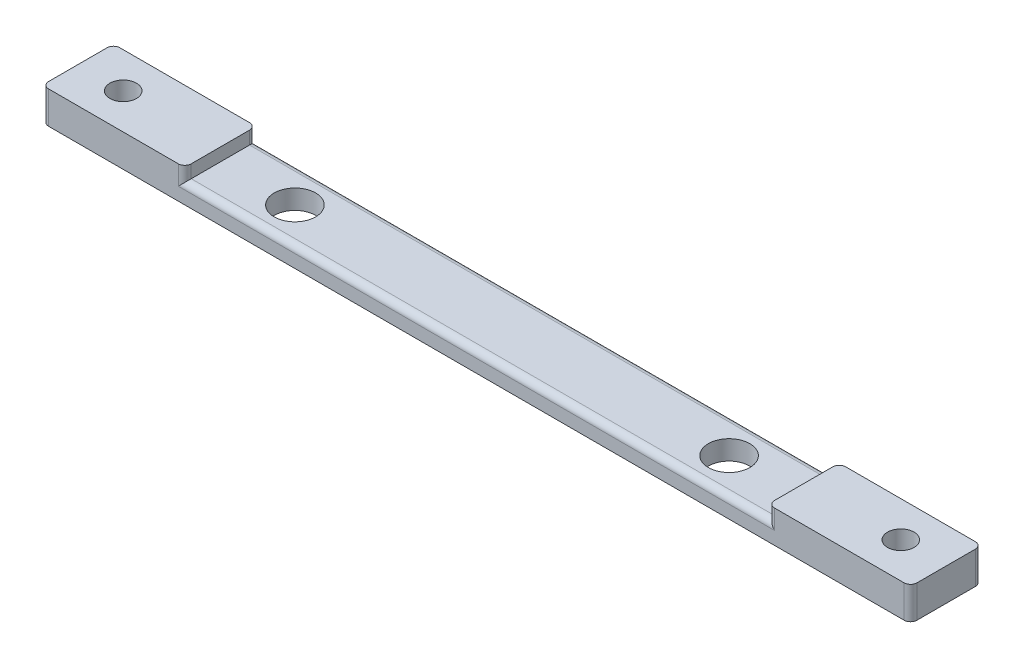
SolidWorks part; units mm, degrees
ref_plane "Plan de face" through (0, 0, 0) normal (0, 0, 1) x (1, 0, 0)
ref_plane "Plan de dessus" through (0, 0, 0) normal (0, 1, 0) x (1, 0, 0)
ref_plane "Plan de droite" through (0, 0, 0) normal (1, 0, 0) x (0, 0, -1)
sketch "Esquisse1" plane through (0, 0, 0) normal (0, 1, 0) x (1, 0, 0)
  line L0 (0, 20.6802) -> (0, -42.2025) construction
  line L1 (0, 0) -> (100.6872, 0) construction
  line L2 (-66, 0) -> (66, 0)
  line L3 (67, 1) -> (67, 10)
  line L4 (66, 11) -> (-66, 11)
  line L5 (24.5168, 5.5) -> (0.5615, 5.5) construction
  line L6 (-67, 1) -> (-67, 10)
  circle A0 centre (60, 5.5) radius 2.05
  circle A1 centre (33.5, 5.5) radius 3.2
  arc A2 (66, 0) -> (67, 1) centre (66, 1) ccw
  arc A3 (67, 10) -> (66, 11) centre (66, 10) ccw
  arc A4 (-67, 10) -> (-66, 11) centre (-66, 10) cw
  arc A5 (-66, 0) -> (-67, 1) centre (-66, 1) cw
  circle A6 centre (-33.5, 5.5) radius 3.2
  circle A7 centre (-60, 5.5) radius 2.05
  point P1 (-67, 11)
  point P9 (0, 0)
  point P17 (67, 0)
  point P20 (67, 11)
  point P31 (0, 11)
  point P32 (-67, 0)
  dimension "D1" = 67
  dimension "D5" = 1
  dimension "D6" = 6.4
  dimension "D7" = 4.1
  dimension "D2" = 33.5
  dimension "D3" = 60
  dimension "D4" = 11
extrude "Boss.-Extru.1" add sketch "Esquisse1" along normal blind 5
sketch "Esquisse2" plane through (0, 0, 0) normal (0, 0, 1) x (1, 0, 0)
  line L0 (0, 18.1819) -> (0, -11.7321) construction
  line L1 (-16.5133, 3) -> (14.2481, 3) construction
  line L2 (-45, 5) -> (-45, 3)
  line L3 (45, 5) -> (45, 3)
  line L4 (-66, 0) -> (66, 0)
  line L5 (66, 0) -> (66, 5)
  line L6 (66, 5) -> (-66, 5)
  line L7 (-66, 5) -> (-66, 0)
  line L8 (-66, 0) -> (66, 0)
  line L9 (66, 0) -> (66, 5)
  line L10 (66, 5) -> (-66, 5)
  line L11 (-66, 5) -> (-66, 0)
  line L12 (-45, 3) -> (45, 3)
  point P13 (0, 3)
  line M10 (66, 5) -> (-66, 5)
  dimension "D2" = 3
  dimension "D3" = 45
  dimension "D1" = 0
extrude "Enlèv. mat.-Extru.1" cut sketch "Esquisse2" against normal through all contours L2 L12 L3 M10
fillet "Congé1" radius 1 6 edges at (0, 3, -11) (45, 4, -11) (45, 4, 0) (0, 3, 0) (-45, 4, -11) (-45, 4, 0)
